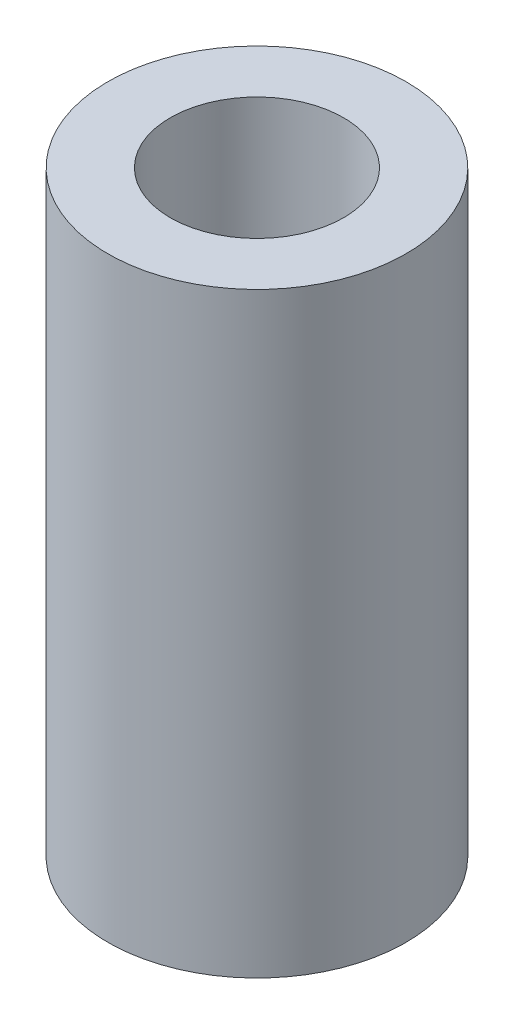
SolidWorks part; units mm, degrees
ref_plane "Front Plane" through (0, 0, 0) normal (0, 0, 1) x (1, 0, 0)
ref_plane "Top Plane" through (0, 0, 0) normal (0, 1, 0) x (1, 0, 0)
ref_plane "Right Plane" through (0, 0, 0) normal (1, 0, 0) x (0, 0, -1)
sketch "Sketch1" plane through (0, 0, 0) normal (0, 1, 0) x (1, 0, 0)
  circle A0 centre (-37.5035, 4.7082) radius 4.7625
  dimension "D1" = 9.525
extrude "Boss-Extrude1" add sketch "Sketch1" along normal blind 19.05
sketch "Sketch2" plane through (0, 19.05, 0) normal (0, 1, 0) x (1, 0, 0)
  circle A0 centre (-37.5035, 4.7082) radius 2.7686
  dimension "D1" = 5.5372
extrude "Cut-Extrude1" cut sketch "Sketch2" against normal blind 19.05
